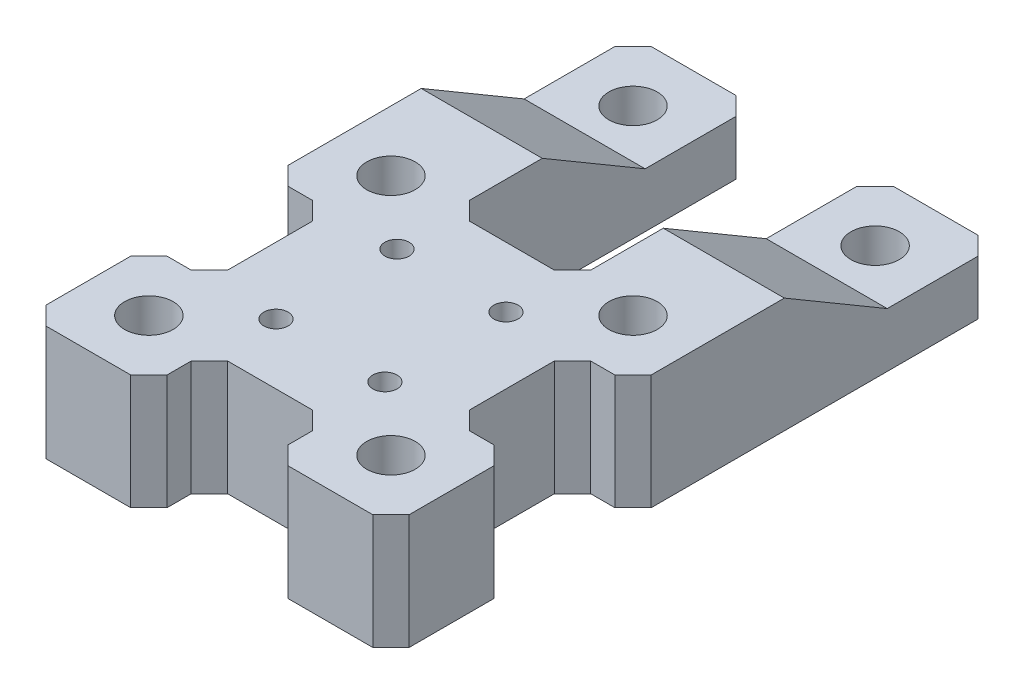
SolidWorks part; units mm, degrees
material "1060 合金"
ref_plane "前视基准面" through (0, 0, 0) normal (0, 0, 1) x (1, 0, 0)
ref_plane "上视基准面" through (0, 0, 0) normal (0, 1, 0) x (1, 0, 0)
ref_plane "右视基准面" through (0, 0, 0) normal (1, 0, 0) x (0, 0, -1)
sketch "草图1" plane through (0, 0, 0) normal (0, 1, 0) x (1, 0, 0)
  line L1 (-30, 50) -> (30, 50)
  line L2 (-30, 50) -> (-30, -50)
  line L3 (-30, -50) -> (30, -50)
  line L4 (30, 50) -> (30, -50)
  circle A0 centre (-20, 0) radius 4
  circle A1 centre (20, 0) radius 4
  circle A2 centre (-20, -40) radius 4
  circle A3 centre (20, -40) radius 4
  circle A4 centre (-20, 40) radius 4
  circle A5 centre (20, 40) radius 4
  circle A6 centre (-9, -30) radius 2
  circle A7 centre (9, -30) radius 2
  circle A8 centre (-9, -10) radius 2
  circle A9 centre (9, -10) radius 2
  point P16 (30, 0)
  point P18 (0, 50)
  dimension "D1" = 8
  dimension "D11" = 4
  dimension "D2" = 40
  dimension "D3" = 40
  dimension "D4" = 60
  dimension "D5" = 100
  dimension "D6" = 40
  dimension "D7" = 20
  dimension "D8" = 40
  dimension "D9" = 20
  dimension "D10" = 18
  dimension "D12" = 9
  dimension "D13" = 20
extrude "凸台-拉伸1" add sketch "草图1" along normal blind 19
sketch "草图3" plane through (0, 0, 0) normal (0, 1, 0) x (1, 0, 0)
  line L0 (30, 50) -> (-30, 50) construction
  line L1 (-10, 50) -> (10, 50)
  line L2 (-10, 50) -> (-10, 0)
  line L3 (-10, 0) -> (10, 0)
  line L4 (10, 50) -> (10, 0)
  line L5 (30, 0) -> (-30, 0) construction
  line L6 (30, -50) -> (30, 50) construction
  line L7 (-30, 50) -> (-30, -50) construction
  line L12 (-30, -50) -> (30, -50) construction
  line L13 (-10, -50) -> (10, -50)
  line L14 (-10, -50) -> (-10, -40)
  line L15 (-10, -40) -> (10, -40)
  line L16 (10, -50) -> (10, -40)
  line L17 (-30, 50) -> (-30, -50) construction
  line L18 (-30, -30) -> (-20, -30)
  line L19 (-30, -30) -> (-30, -10)
  line L20 (-30, -10) -> (-20, -10)
  line L21 (-20, -30) -> (-20, -10)
  line L22 (30, -50) -> (30, 50) construction
  line L23 (30, -30) -> (20, -30)
  line L24 (30, -30) -> (30, -10)
  line L25 (30, -10) -> (20, -10)
  line L26 (20, -30) -> (20, -10)
  line L27 (-30, -50) -> (30, -50) construction
  point P12 (0, 50)
  dimension "D1" = 20
  dimension "D2" = 50
  dimension "D3" = 10
  dimension "D4" = 10
  dimension "D5" = 10
  dimension "D6" = 20
  dimension "D7" = 20
extrude "切除-拉伸1" cut sketch "草图3" along normal through all
chamfer "倒角1" distance 3 angle 45 20 edges at (30, 9.5, 50) (-30, 9.5, 50) (-30, 9.5, -50) (30, 9.5, -50) (10, 9.5, 0) (-10, 9.5, 0) (10, 9.5, -50) (-10, 9.5, -50) (10, 9.5, 50) (10, 9.5, 40) (-10, 9.5, 40) (-10, 9.5, 50) (20, 9.5, 30) (30, 9.5, 30) (20, 9.5, 10) (30, 9.5, 10) (-20, 9.5, 10) (-30, 9.5, 10) (-20, 9.5, 30) (-30, 9.5, 30)
sketch "草图4" plane through (0, 0, 0) normal (1, 0, 0) x (0, 0, -1)
  line L1 (15, 19) -> (32, 9)
  line L3 (32, 9) -> (50, 9)
  line L10 (50, 19) -> (15, 19)
  line L11 (-47, 19) -> (-33, 19) construction
  line L13 (50, 19) -> (50, 0) construction
  line L14 (50, 9) -> (50, 19)
  dimension "D1" = 10
  dimension "D2" = 35
  dimension "D3" = 18
extrude "切除-拉伸2" cut sketch "草图4" against normal through all both and the other way through all
